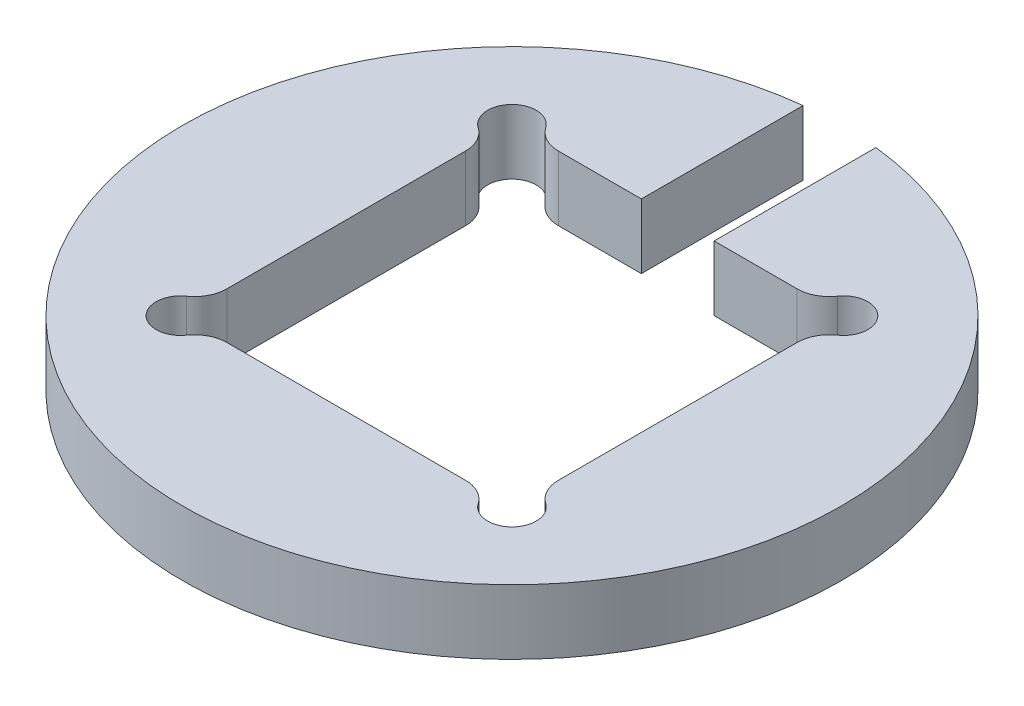
SolidWorks part; units mm, degrees
ref_plane "Front Plane" through (0, 0, 0) normal (0, 0, 1) x (1, 0, 0)
ref_plane "Top Plane" through (0, 0, 0) normal (0, 1, 0) x (1, 0, 0)
ref_plane "Right Plane" through (0, 0, 0) normal (1, 0, 0) x (0, 0, -1)
sketch "Sketch1" plane through (0, 0, 0) normal (0, 1, 0) x (1, 0, 0)
  line L0 (0, 0) -> (0, 20.5)
  line L1 (0, 20.5) -> (8, 20.5)
  line L2 (8, 20.5) -> (8, 30.5)
  line L3 (0, 0) -> (20.5, 0)
  line L4 (20.5, 0) -> (20.5, 20.5)
  line L5 (20.5, 20.5) -> (12.5, 20.5)
  line L6 (12.5, 20.5) -> (12.5, 30.5)
  line L7 (0, 10.25) -> (20.5, 10.25) construction
  arc A2 (12.5, 30.5) -> (8, 30.5) centre (10.25, 10.25) cw
  arc A3 (19, 20.5) -> (20.5, 19) centre (20.5, 20.5) cw
  arc A4 (20.5, 1.5) -> (19, 0) centre (20.5, 0) cw
  arc A5 (1.5, 0) -> (0, 1.5) centre (0, 0) cw
  arc A6 (1.5, 20.5) -> (0, 19) centre (0, 20.5) ccw
  dimension "D1" = 20.5
  dimension "D7" = 1.5
  dimension "D5" = 1.5
  dimension "D8" = 1.5
  dimension "D9" = 1.5
  dimension "D2" = 20.5
  dimension "D3" = 4.5
  dimension "D4" = 10
  dimension "D6" = 8
extrude "Boss-Extrude1" add sketch "Sketch1" along normal blind 4 contours A6 L1 L2 A2 L6 L5 A3 L4 A4 L3 A5 L0
fillet "Fillet1" radius 2 8 edges at (19, 2, 0) (20.5, 2, -1.5) (20.5, 2, -19) (0, 2, -1.5) (1.5, 2, 0) (0, 2, -19) (19, 2, -20.5) (1.5, 2, -20.5)
